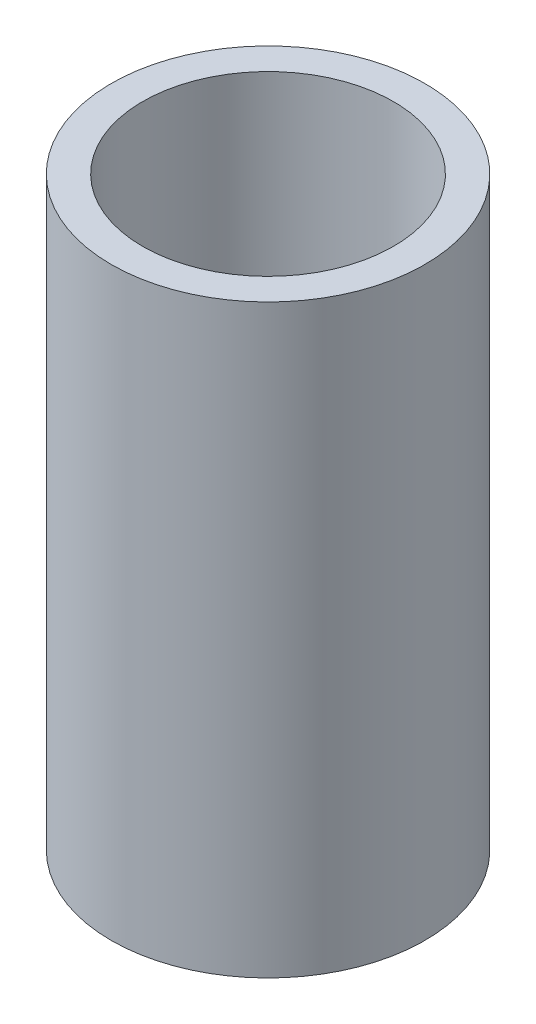
SolidWorks part; units mm, degrees
ref_plane "Front Plane" through (0, 0, 0) normal (0, 0, 1) x (1, 0, 0)
ref_plane "Top Plane" through (0, 0, 0) normal (0, 1, 0) x (1, 0, 0)
ref_plane "Right Plane" through (0, 0, 0) normal (1, 0, 0) x (0, 0, -1)
sketch "Sketch1" plane through (0, 0, 0) normal (0, 1, 0) x (1, 0, 0)
  circle A0 centre (0, 0) radius 6
  circle A1 centre (0, 0) radius 7.5
  dimension "D1" = 12
  dimension "D2" = 15
extrude "Boss-Extrude1" add sketch "Sketch1" along normal mid plane 28
